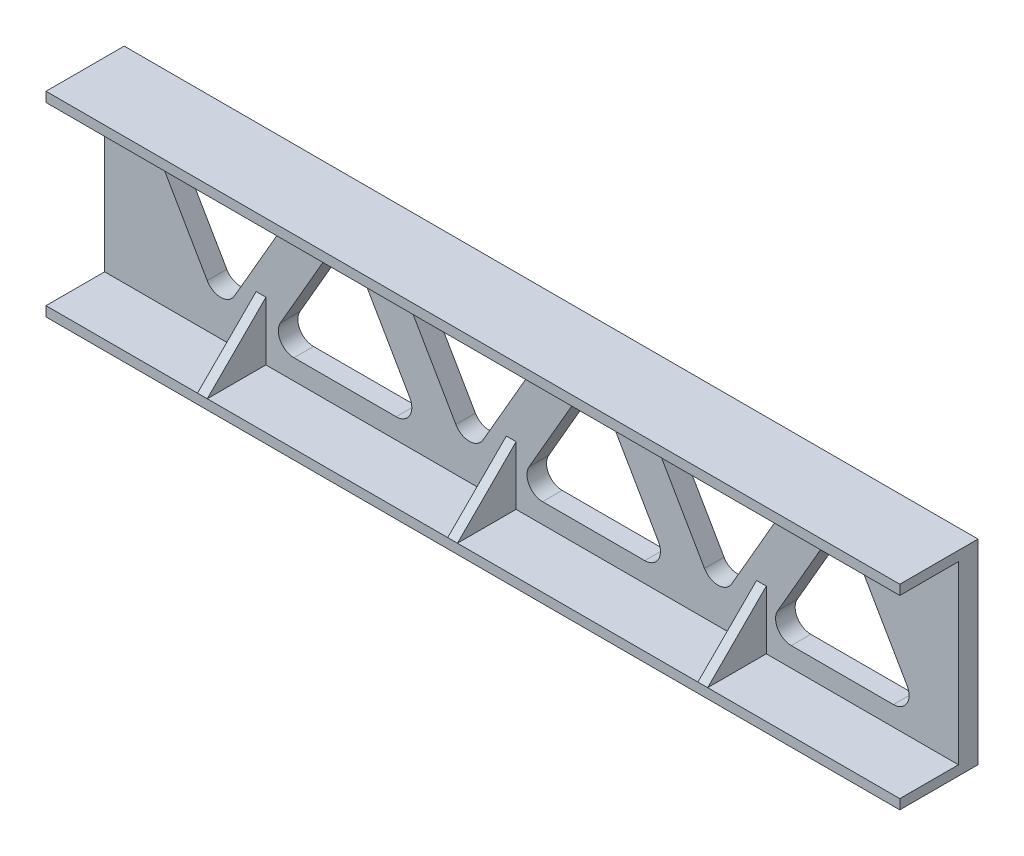
SolidWorks part; units mm, degrees
material "Nylon 6/10"
ref_plane "Front Plane" through (0, 0, 0) normal (0, 0, 1) x (1, 0, 0)
ref_plane "Top Plane" through (0, 0, 0) normal (0, 1, 0) x (1, 0, 0)
ref_plane "Right Plane" through (0, 0, 0) normal (1, 0, 0) x (0, 0, -1)
sketch "Sketch2" plane through (0, 0, 0) normal (0, 0, 1) x (1, 0, 0)
  line L0 (-5.1244, 14.6538) -> (267.1636, 14.6538)
  line L1 (269.7036, 17.1938) -> (269.7036, 75.6138)
  line L2 (267.1636, 78.1538) -> (-5.1244, 78.1538)
  line L3 (-7.6644, 75.6138) -> (-7.6644, 17.1938)
  line L4 (30.0546, 24.4068) -> (30.0546, 68.4009) construction
  line L5 (-7.6644, 46.4038) -> (269.7036, 46.4038) construction
  line L6 (30.0546, 24.4068) -> (4.6546, 68.4009)
  line L7 (55.4546, 68.4009) -> (4.6546, 68.4009)
  line L8 (55.4546, 68.4009) -> (30.0546, 24.4068)
  line L9 (70.4406, 68.4009) -> (95.8406, 24.4068)
  line L10 (45.0406, 24.4068) -> (95.8406, 24.4068)
  line L11 (45.0406, 24.4068) -> (70.4406, 68.4009)
  line L12 (70.4406, 24.4068) -> (70.4406, 68.4009)
  line L13 (110.8263, 24.3058) -> (85.4263, 68.2999)
  line L14 (136.2263, 68.2999) -> (85.4263, 68.2999)
  line L15 (136.2263, 68.2999) -> (110.8263, 24.3058)
  line L16 (125.8123, 24.3058) -> (151.2123, 68.2999)
  line L17 (151.2123, 68.2999) -> (176.6123, 24.3058)
  line L18 (125.8123, 24.3058) -> (176.6123, 24.3058)
  line L19 (191.5979, 24.2049) -> (166.1979, 68.199)
  line L20 (216.9979, 68.199) -> (166.1979, 68.199)
  line L21 (216.9979, 68.199) -> (191.5979, 24.2049)
  line L22 (206.5839, 24.2049) -> (231.9839, 68.199)
  line L23 (231.9839, 68.199) -> (257.3839, 24.2049)
  line L24 (206.5839, 24.2049) -> (257.3839, 24.2049)
  arc A0 (267.1636, 14.6538) -> (269.7036, 17.1938) centre (267.1636, 17.1938) ccw
  arc A1 (269.7036, 75.6138) -> (267.1636, 78.1538) centre (267.1636, 75.6138) ccw
  arc A2 (-5.1244, 14.6538) -> (-7.6644, 17.1938) centre (-5.1244, 17.1938) cw
  arc A3 (-5.1244, 78.1538) -> (-7.6644, 75.6138) centre (-5.1244, 75.6138) ccw
  point P0 (30.0546, 46.4038)
  point P15 (70.4406, 46.4038)
  point P30 (269.7036, 14.6538)
  point P33 (269.7036, 78.1538)
  point P36 (-7.6644, 14.6538)
  point P39 (-7.6644, 78.1538)
  dimension "D28" = 2.54
  dimension "D1" = 63.5
  dimension "D2" = 277.368
  dimension "D3" = 50.8
  dimension "D4" = 50.8
  dimension "D5" = 50.8
  dimension "D6" = 21.997
  dimension "D7" = 90
  dimension "D8" = 270
  dimension "D9" = 300
  dimension "D10" = 300
  dimension "D11" = 0
  dimension "D13" = 14.986
  dimension "D14" = 14.986
  dimension "D15" = 50.8
  dimension "D16" = 50.8
  dimension "D17" = 50.8
  dimension "D18" = 50.8
  dimension "D19" = 50.8
  dimension "D20" = 300
  dimension "D21" = 12.319
  dimension "D22" = 9.652
  dimension "D23" = 63.5
  dimension "D24" = 270
  dimension "D25" = 9.753
  dimension "D26" = 9.753
  dimension "D27" = 12.3197
  dimension "D12" = 3
extrude "Boss-Extrude1" add sketch "Sketch2" along normal blind 6.35 contours L2 L3 L0 L1 L24 L22 L23 L18 L16 L17 L7 L8 L6 L10 L11 L9 L14 L15 L13 L20 L21 L19
fillet "Fillet1" radius 5.08 18 edges at (30.0546, 24.4068, 3.175) (191.5979, 24.2049, 3.175) (110.8263, 24.3058, 3.175) (151.2123, 68.2999, 3.175) (231.9839, 68.199, 3.175) (166.1979, 68.199, 3.175) (85.4263, 68.2999, 3.175) (206.5839, 24.2049, 3.175) (125.8123, 24.3058, 3.175) (45.0406, 24.4068, 3.175) (257.3839, 24.2049, 3.175) (176.6123, 24.3058, 3.175) (95.8406, 24.4068, 3.175) (70.4406, 68.4009, 3.175) (4.6546, 68.4009, 3.175) (55.4546, 68.4009, 3.175) (136.2263, 68.2999, 3.175) (216.9979, 68.199, 3.175)
ref_plane "Plane1" through (0, 78.1538, 0) normal (0, 1, 0) x (1, 0, 0)
sketch "Sketch3" plane through (0, 78.1538, 0) normal (0, 1, 0) x (1, 0, 0)
  line L0 (-7.6644, 0) -> (269.7036, 0)
  line L1 (269.7036, 0) -> (269.7036, -25.4)
  line L2 (269.7036, -25.4) -> (-7.6644, -25.4)
  line L3 (-7.6644, -25.4) -> (-7.6644, 0)
extrude "Boss-Extrude2" add sketch "Sketch3" against normal blind 3.175
ref_plane "Plane2" through (0, 14.6538, 0) normal (0, -1, 0) x (-1, 0, 0)
sketch "Sketch5" plane through (0, 14.6538, 0) normal (0, -1, 0) x (-1, 0, 0)
  line L0 (-269.7036, 0) -> (7.6644, 0)
  line L1 (7.6644, 0) -> (7.6644, -25.4)
  line L2 (7.6644, -25.4) -> (-269.7036, -25.4)
  line L3 (-269.7036, -25.4) -> (-269.7036, 0)
extrude "Boss-Extrude3" add sketch "Sketch5" against normal blind 3.175
ref_plane "Plane3" through (269.7036, 74.9788, 6.35) normal (1, 0, 0) x (0, 0, -1)
sketch "Sketch7" plane through (0, 0, 6.35) normal (0, 0, 1) x (1, 0, 0)
  line L0 (-7.6644, 17.8288) -> (43.1356, 17.8288) construction
  line L1 (269.7036, 17.8288) -> (-7.6644, 17.8288) construction
  line L2 (43.1356, 17.8288) -> (124.4156, 17.8288) construction
  line L3 (269.7036, 17.8288) -> (-7.6644, 17.8288) construction
  line L4 (124.4156, 17.8288) -> (205.6956, 17.8288) construction
  line L5 (43.1356, 17.8288) -> (43.1356, 43.2288) construction
  line L6 (124.4156, 17.8288) -> (124.4156, 43.2288) construction
  line L7 (205.6956, 17.8288) -> (205.6956, 43.2288) construction
  line L8 (269.7036, 74.9788) -> (218.1336, 74.9788) construction
  line L9 (-7.6644, 74.9788) -> (269.7036, 74.9788) construction
  line L10 (218.1336, 74.9788) -> (135.6529, 74.9788) construction
  line L11 (-7.6644, 74.9788) -> (269.7036, 74.9788) construction
  line L12 (135.6529, 74.9788) -> (54.3729, 74.9788) construction
  line L13 (218.1336, 74.9788) -> (218.1336, 49.5788) construction
  line L14 (135.6529, 74.9788) -> (135.6529, 49.5788) construction
  line L15 (54.3729, 74.9788) -> (54.3729, 49.5788) construction
ref_plane "Plane4" through (54.3729, 0, 0) normal (-1, 0, 0) x (0, 0, 1)
ref_plane "Plane5" through (43.1356, 0, 0) normal (1, 0, 0) x (0, 0, -1)
ref_plane "Plane6" through (135.6529, 0, 0) normal (-1, 0, 0) x (0, 0, 1)
ref_plane "Plane7" through (124.4156, 0, 0) normal (1, 0, 0) x (0, 0, -1)
ref_plane "Plane8" through (205.6956, 0, 0) normal (1, 0, 0) x (0, 0, -1)
ref_plane "Plane9" through (218.1336, 0, 0) normal (-1, 0, 0) x (0, 0, 1)
sketch "Sketch8" plane through (43.1356, 0, 0) normal (1, 0, 0) x (0, 0, -1)
  line L0 (-25.4, 17.8288) -> (-6.35, 17.8288)
  line L1 (-6.35, 17.8288) -> (-6.35, 36.8788)
  line L2 (-6.35, 17.8288) -> (-6.35, 74.9788) construction
  line L3 (-6.35, 36.8788) -> (-25.4, 17.8288)
extrude "Boss-Extrude4" add sketch "Sketch8" along normal blind 1.5875 and the other way blind 1.5875
sketch "Sketch9" plane through (124.4156, 0, 0) normal (1, 0, 0) x (0, 0, -1)
  line L0 (-25.4, 17.8288) -> (-6.35, 17.8288)
  line L1 (-6.35, 17.8288) -> (-6.35, 36.8788)
  line L2 (-6.35, 36.8788) -> (-25.4, 17.8288)
sketch "Sketch10" plane through (205.6956, 0, 0) normal (1, 0, 0) x (0, 0, -1)
  line L0 (-25.4, 17.8288) -> (-6.35, 17.8288)
  line L1 (-6.35, 17.8288) -> (-6.35, 36.8788)
  line L2 (-6.35, 36.8788) -> (-25.4, 17.8288)
sketch "Sketch11" plane through (218.1336, 0, 0) normal (-1, 0, 0) x (0, 0, 1)
  line L0 (25.4, 74.9788) -> (6.35, 74.9788)
  line L1 (6.35, 74.9788) -> (6.35, 55.9288)
  line L2 (6.35, 74.9788) -> (6.35, 17.8288) construction
  line L3 (6.35, 55.9288) -> (25.4, 74.9788)
sketch "Sketch12" plane through (135.6529, 0, 0) normal (-1, 0, 0) x (0, 0, 1)
  line L0 (25.4, 74.9788) -> (6.35, 74.9788)
  line L1 (6.35, 74.9788) -> (6.35, 55.9288)
  line L2 (6.35, 55.9288) -> (25.4, 74.9788)
sketch "Sketch13" plane through (54.3729, 0, 0) normal (-1, 0, 0) x (0, 0, 1)
  line L0 (25.4, 74.9788) -> (6.35, 74.9788)
  line L1 (6.35, 74.9788) -> (6.35, 55.9288)
  line L2 (6.35, 55.9288) -> (25.4, 74.9788)
extrude "Boss-Extrude5" add sketch "Sketch9" along normal blind 1.5875 and the other way blind 1.5875
extrude "Boss-Extrude6" add sketch "Sketch10" along normal blind 1.5875 and the other way blind 1.5875
extrude "Boss-Extrude7" add sketch "Sketch11" along normal blind 1.5875 and the other way blind 1.5875
extrude "Boss-Extrude8" add sketch "Sketch12" along normal blind 1.5875 and the other way blind 1.5875
extrude "Boss-Extrude9" add sketch "Sketch13" along normal blind 1.5875 and the other way blind 1.5875
